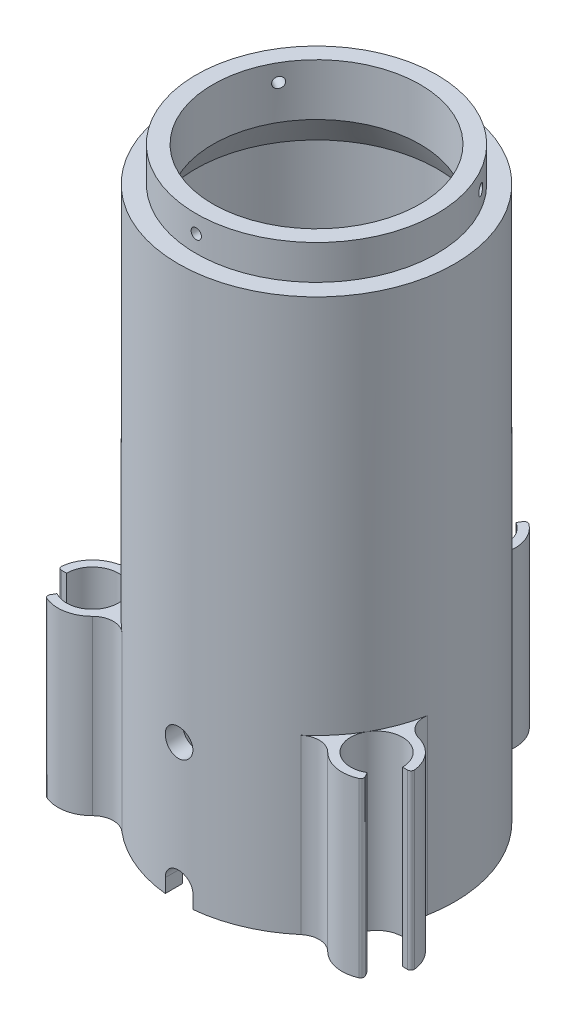
SolidWorks part; units mm, degrees
ref_plane "Front Plane" through (0, 0, 0) normal (0, 0, 1) x (1, 0, 0)
ref_plane "Top Plane" through (0, 0, 0) normal (0, 1, 0) x (1, 0, 0)
ref_plane "Right Plane" through (0, 0, 0) normal (1, 0, 0) x (0, 0, -1)
sketch "Sketch1" plane through (0, 0, 0) normal (0, 1, 0) x (1, 0, 0)
  circle A0 centre (0, 0) radius 40
  circle A1 centre (0, 0) radius 35
  dimension "D1" = 80
  dimension "D2" = 70
extrude "Boss-Extrude1" add sketch "Sketch1" along normal blind 180
sketch "Sketch3" plane through (0, 0, 0) normal (1, 0, 0) x (0, 0, -1)
  line L0 (35, 180) -> (-35, 180) construction
  line L1 (35, 180) -> (-35, 180) construction
  line L2 (-35, 180) -> (-40, 180)
  line L3 (-40, 180) -> (-40, 185)
  line L5 (0, -20.1549) -> (0, 315.4905) construction
  line L10 (0, 210) -> (-20, 210)
  line L11 (-40, 185) -> (-35, 180) construction
  line L12 (0, 210) -> (0, 202.9289)
  line L13 (0, 202.9289) -> (-20, 202.9289)
  line L14 (-20, 210) -> (-20, 202.9289) construction
  line L15 (-32.1, 200.5) -> (-32.1, 189.75) construction
  line L16 (-40, 185) -> (-32.1, 189.75) construction
  spline S0 degree 2 poles (-20, 210) (-35.4489, 201.9814) (-40, 185) knots 0 0 0 1 1 1
  spline S1 degree 2 poles (-20, 202.9289) (-32.9895, 194.5779) (-35, 180) knots 0 0 0 1 1 1
  dimension "D6" = 9.2181
  dimension "D4" = 7.9
  dimension "D3" = 30
  dimension "D1" = 20
  dimension "D2" = 5
  dimension "D5" = 15.5
revolve "Revolve1" add sketch "Sketch3" angle 360 about L5
sketch "Sketch4" plane through (0, 0, 0) normal (0, 1, 0) x (1, 0, 0)
  line L0 (89.2824, 0) -> (-73.0822, 0) construction
  line L1 (0, -55.578) -> (0, 54.7041) construction
  line L2 (0, 47.5) -> (-5, 56.1603) construction
  line L3 (0, 47.5) -> (5, 56.1603) construction
  line L4 (4.4721, 55.246) -> (3.75, 53.9952)
  line L5 (-4.4721, 55.246) -> (-3.75, 53.9952)
  line L6 (45.6083, -31.496) -> (44.8862, -30.2452)
  line L7 (50.0805, -23.75) -> (48.6362, -23.75)
  line L8 (-50.0805, -23.75) -> (-48.6362, -23.75)
  line L9 (-45.6083, -31.496) -> (-44.8862, -30.2452)
  line L10 (-13.432, 37.6773) -> (13.432, 37.6773)
  line L11 (39.3455, -7.2063) -> (25.9136, -30.4711)
  line L12 (-39.3455, -7.2063) -> (-25.9136, -30.4711)
  circle A0 centre (0, 0) radius 40 construction
  arc A1 (13.432, 37.6773) -> (6.0523, 39.5395) centre (0, 0) ccw construction
  arc A2 (-3.75, 53.9952) -> (3.75, 53.9952) centre (0, 47.5) ccw
  arc A4 (9.6542, 44.8931) -> (5.9313, 55.5511) centre (0, 47.5) ccw
  arc A5 (-40, 0) -> (0, -40) centre (0, 0) ccw construction
  arc A6 (0, -40) -> (40, 0) centre (0, 0) ccw construction
  arc A7 (0, 37.5) -> (1.875, 37.6773) centre (0, 47.5) ccw construction
  arc A8 (-1.875, 37.6773) -> (0, 37.5) centre (0, 47.5) ccw construction
  arc A9 (-13.432, 37.6773) -> (-9.6542, 44.8931) centre (-15.4468, 43.3289) ccw
  arc A10 (-9.6542, 44.8931) -> (-13.432, 37.6773) centre (-15.4468, 43.3289) ccw construction
  arc A11 (-13.432, 37.6773) -> (-40, 0) centre (0, 0) ccw construction
  arc A12 (-9.6542, 44.8931) -> (-6.0523, 39.5395) centre (0, 47.5) ccw construction
  arc A13 (9.6542, 44.8931) -> (13.432, 37.6773) centre (15.4468, 43.3289) ccw
  arc A14 (13.432, 37.6773) -> (9.6542, 44.8931) centre (15.4468, 43.3289) ccw construction
  arc A15 (6.0523, 39.5395) -> (9.6542, 44.8931) centre (0, 47.5) ccw construction
  arc A16 (-6.0523, 39.5395) -> (-13.432, 37.6773) centre (0, 0) ccw construction
  arc A17 (6.0523, 39.5395) -> (0, 40) centre (0, 0) ccw construction
  arc A18 (0, 40) -> (-6.0523, 39.5395) centre (0, 0) ccw construction
  arc A19 (40, 0) -> (13.432, 37.6773) centre (0, 0) ccw construction
  arc A20 (-5.9313, 55.5511) -> (-9.6542, 44.8931) centre (0, 47.5) ccw
  arc A21 (5, 56.1603) -> (-5, 56.1603) centre (0, 47.5) ccw construction
  arc A22 (3.75, 53.9952) -> (-3.75, 53.9952) centre (0, 47.5) ccw construction
  arc A23 (5.9313, 55.5511) -> (4.4721, 55.246) centre (5.3382, 54.746) ccw
  arc A24 (-5.9313, 55.5511) -> (-4.4721, 55.246) centre (-5.3382, 54.746) cw
  arc A25 (37.2683, -14.5283) -> (39.3455, -7.2063) centre (0, 0) ccw construction
  arc A27 (39.3455, -7.2063) -> (43.7057, -14.0857) centre (45.2473, -8.2872) ccw
  arc A28 (51.0743, -22.6389) -> (43.7057, -14.0857) centre (41.1362, -23.75) ccw
  arc A30 (25.9136, -30.4711) -> (31.2161, -25.0112) centre (0, 0) ccw construction
  arc A31 (34.0514, -30.8073) -> (25.9136, -30.4711) centre (29.8006, -35.0418) ccw
  arc A32 (34.0514, -30.8073) -> (45.143, -32.9122) centre (41.1362, -23.75) ccw
  arc A33 (48.6362, -23.75) -> (44.8862, -30.2452) centre (41.1362, -23.75) ccw
  arc A34 (45.143, -32.9122) -> (45.6083, -31.496) centre (44.7423, -31.996) ccw
  arc A35 (51.0743, -22.6389) -> (50.0805, -23.75) centre (50.0805, -22.75) cw
  arc A36 (-31.2161, -25.0112) -> (-25.9136, -30.4711) centre (0, 0) ccw construction
  arc A38 (-25.9136, -30.4711) -> (-34.0514, -30.8073) centre (-29.8006, -35.0418) ccw
  arc A39 (-45.143, -32.9122) -> (-34.0514, -30.8073) centre (-41.1362, -23.75) ccw
  arc A41 (-39.3455, -7.2063) -> (-37.2683, -14.5283) centre (0, 0) ccw construction
  arc A42 (-43.7057, -14.0857) -> (-39.3455, -7.2063) centre (-45.2473, -8.2872) ccw
  arc A43 (-43.7057, -14.0857) -> (-51.0743, -22.6389) centre (-41.1362, -23.75) ccw
  arc A44 (-44.8862, -30.2452) -> (-48.6362, -23.75) centre (-41.1362, -23.75) ccw
  arc A45 (-51.0743, -22.6389) -> (-50.0805, -23.75) centre (-50.0805, -22.75) ccw
  arc A46 (-45.143, -32.9122) -> (-45.6083, -31.496) centre (-44.7423, -31.996) cw
  arc A47 (1.875, 37.6773) -> (6.0523, 39.5395) centre (0, 47.5) ccw construction
  arc A48 (-6.0523, 39.5395) -> (-1.875, 37.6773) centre (0, 47.5) ccw construction
  arc A49 (37.2683, -14.5283) -> (33.567, -17.2149) centre (41.1362, -23.75) ccw construction
  arc A50 (31.6921, -20.4624) -> (31.2161, -25.0112) centre (41.1362, -23.75) ccw construction
  arc A51 (32.476, -18.75) -> (31.6921, -20.4624) centre (41.1362, -23.75) ccw [skipped]
  arc A52 (33.567, -17.2149) -> (32.476, -18.75) centre (41.1362, -23.75) ccw [skipped]
  arc A53 (-31.2161, -25.0112) -> (-31.6921, -20.4624) centre (-41.1362, -23.75) ccw construction
  arc A54 (-33.567, -17.2149) -> (-37.2683, -14.5283) centre (-41.1362, -23.75) ccw construction
  arc A55 (-31.6921, -20.4624) -> (-32.476, -18.75) centre (-41.1362, -23.75) ccw [skipped]
  arc A56 (-32.476, -18.75) -> (-33.567, -17.2149) centre (-41.1362, -23.75) ccw [skipped]
  dimension "D1" = 15
  dimension "D2" = 20
  dimension "D3" = 12
  dimension "D4" = 12
  dimension "D7" = 1
  dimension "D5" = 30
  dimension "D6" = 30
  dimension "D8" = 3
extrude "Boss-Extrude2" add sketch "Sketch4" along normal blind 50
ref_plane "Plane1" through (0, 70, 0) normal (0, 1, 0) x (1, 0, 0)
sketch "Sketch6" plane through (0, 70, 0) normal (0, 1, 0) x (1, 0, 0)
  line L0 (0, -46.0373) -> (0, 62.5131) construction
  line L1 (66.4114, 0) -> (-65.7318, 0) construction
  line L2 (-5, 34.641) -> (-5, 11.4564)
  line L3 (5, 34.641) -> (5, 11.4564)
  line L4 (0, 0) -> (62.2869, -35.9614) construction
  line L5 (0, 0) -> (-61.7339, -35.6421) construction
  line L6 (32.9487, -11.8061) -> (12.5, 0)
  line L7 (26.6987, -22.6314) -> (6.25, -10.8253)
  line L8 (-26.6987, -22.6314) -> (-6.25, -10.8253)
  line L9 (-12.5, 0) -> (-32.9487, -11.8061)
  circle A0 centre (0, 0) radius 35 construction
  arc A1 (-32.9487, -11.8061) -> (-26.6987, -22.6314) centre (0, 0) ccw
  arc A2 (12.5, 0) -> (5, 11.4564) centre (0, 0) ccw
  arc A3 (-5, 34.641) -> (-35, 0) centre (0, 0) ccw construction
  arc A4 (-35, 0) -> (-32.9487, -11.8061) centre (0, 0) ccw construction
  arc A5 (26.6987, -22.6314) -> (32.9487, -11.8061) centre (0, 0) ccw
  arc A6 (-26.6987, -22.6314) -> (0, -35) centre (0, 0) ccw construction
  arc A7 (0, -35) -> (26.6987, -22.6314) centre (0, 0) ccw construction
  arc A8 (5, 34.641) -> (-5, 34.641) centre (0, 0) ccw
  arc A9 (32.9487, -11.8061) -> (35, 0) centre (0, 0) ccw construction
  arc A10 (35, 0) -> (5, 34.641) centre (0, 0) ccw construction
  arc A11 (6.25, -10.8253) -> (10.8253, -6.25) centre (0, 0) ccw construction
  arc A12 (10.8253, -6.25) -> (12.5, 0) centre (0, 0) ccw construction
  arc A13 (-5, 11.4564) -> (-12.5, 0) centre (0, 0) ccw
  arc A14 (5, 11.4564) -> (0, 12.5) centre (0, 0) ccw construction
  arc A15 (0, 12.5) -> (-5, 11.4564) centre (0, 0) ccw construction
  arc A16 (-6.25, -10.8253) -> (6.25, -10.8253) centre (0, 0) ccw
  arc A17 (-12.5, 0) -> (-10.8253, -6.25) centre (0, 0) ccw construction
  arc A18 (-10.8253, -6.25) -> (-6.25, -10.8253) centre (0, 0) ccw construction
  circle A19 centre (0, 0) radius 5.5
  dimension "D1" = 25
  dimension "D5" = 11
  dimension "D2" = 10
  dimension "D3" = 30
  dimension "D4" = 30
extrude "Boss-Extrude3" add sketch "Sketch6" along normal blind 8
sketch "Sketch7" plane through (0, 78, 0) normal (0, 1, 0) x (1, 0, 0)
  line L0 (0, 0) -> (0, 18.4139) construction
  circle A0 centre (0, 0) radius 8 construction
  circle A1 centre (0, 8) radius 1.55
  circle A2 centre (8, 0) radius 1.55
  circle A3 centre (0, -8) radius 1.55
  circle A4 centre (-8, 0) radius 1.55
  dimension "D1" = 16
  dimension "D2" = 3.1
  dimension "D3" = 4
extrude "Cut-Extrude1" cut sketch "Sketch7" against normal up to next
sketch "Sketch9" plane through (0, 210, 0) normal (0, 1, 0) x (1, 0, 0)
  circle A0 centre (0, 0) radius 40 construction
  circle A1 centre (0, 0) radius 40
extrude "Cut-Extrude2" cut sketch "Sketch9" against normal blind 50
sketch "Sketch10" plane through (0, 0, 0) normal (0, 0, 1) x (1, 0, 0)
  line L0 (35, 160) -> (-35, 160) construction
  line L1 (35, 160) -> (-35, 160) construction
  line L2 (-35, 146.3397) -> (-30, 155)
  line L3 (-30, 155) -> (-30, 170)
  line L4 (-30, 170) -> (-34.85, 170)
  line L5 (-35, 170) -> (-35, 160) construction
  line L6 (-35, 160) -> (-35, 146.3397)
  line L7 (0, 0) -> (0, 240.5524) construction
  line L9 (-34.85, 160) -> (-34.85, 170)
  line L10 (-34.85, 160) -> (-35, 160)
  line L11 (-34.85, 170) -> (-35, 170) construction
  dimension "D1" = 10
  dimension "D2" = 5
  dimension "D3" = 30
  dimension "D4" = 5
  dimension "D5" = 0.15
revolve "Revolve2" add sketch "Sketch10" angle 360 about L7
ref_plane "Plane2" through (0, 0, 40) normal (0, 0, 1) x (1, 0, 0)
sketch "Sketch11" plane through (0, 0, 40) normal (0, 0, 1) x (1, 0, 0)
  line L1 (40, 160) -> (-40, 160) construction
  line L2 (0, 0) -> (0, 229.7967) construction
  line L3 (40, 160) -> (-40, 160) construction
  circle A0 centre (0, 165) radius 1.5
  circle A1 centre (0, 165) radius 3 construction
  dimension "D1" = 3
  dimension "D3" = 6
  dimension "D2" = 5
extrude "Cut-Extrude3" cut sketch "Sketch11" against normal up to next
pattern_circular "CirPattern1" count 3 over 360 about axis through (0, 170, 0) along (0, -1, 0) of "Cut-Extrude3"
sketch "Sketch12" plane through (0, 0, 40) normal (0, 0, 1) x (1, 0, 0)
  line L0 (0, 0) -> (0, 124.7161) construction
  line L1 (-25.9136, 0) -> (25.9136, 0) construction
  line L2 (-4, 0) -> (4, 0)
  line L3 (-4, 4) -> (-4, 0)
  line L4 (4, 4) -> (4, 0)
  line L5 (-25.9136, 0) -> (-4, 0) construction
  line L6 (4, 0) -> (25.9136, 0) construction
  circle A0 centre (0, 40) radius 4
  arc A1 (4, 4) -> (-4, 4) centre (0, 4) ccw
  arc A2 (-4, 4) -> (0, 0) centre (0, 4) ccw construction
  arc A3 (0, 0) -> (4, 4) centre (0, 4) ccw construction
  dimension "D1" = 8
  dimension "D2" = 40
extrude "Cut-Extrude4" cut sketch "Sketch12" against normal up to next
